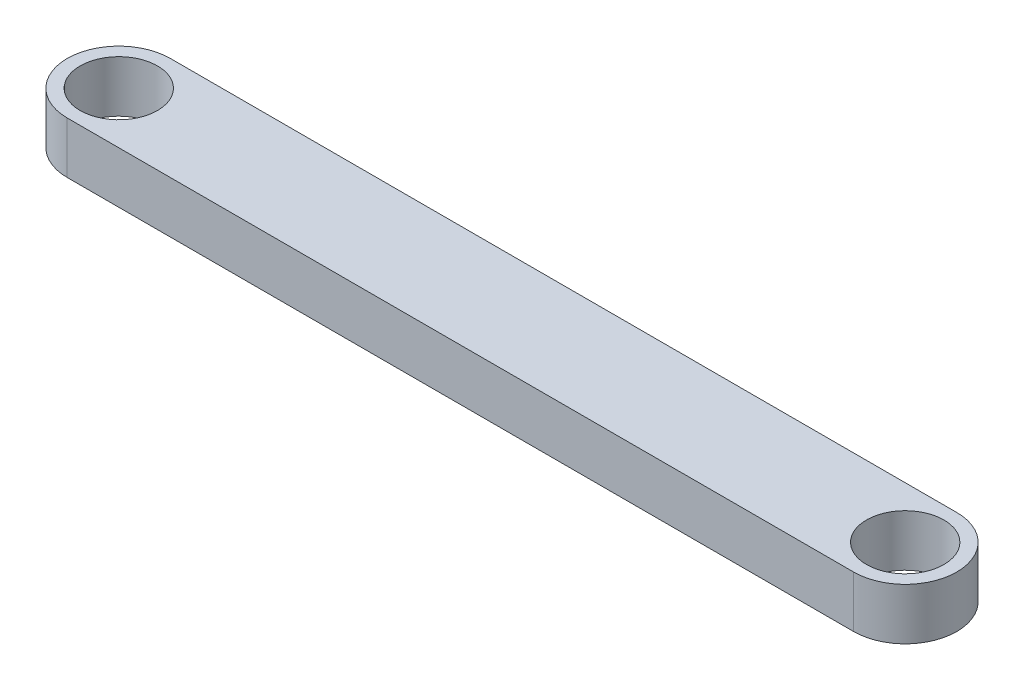
SolidWorks part; units mm, degrees
ref_plane "Front Plane" through (0, 0, 0) normal (0, 0, 1) x (1, 0, 0)
ref_plane "Top Plane" through (0, 0, 0) normal (0, 1, 0) x (1, 0, 0)
ref_plane "Right Plane" through (0, 0, 0) normal (1, 0, 0) x (0, 0, -1)
sketch "Sketch1" plane through (0, 0, 0) normal (0, 1, 0) x (1, 0, 0)
  line L0 (-97.4302, 24.3369) -> (-66.9302, 24.3369)
  line L1 (-66.9302, 20.3369) -> (-97.4302, 20.3369)
  arc A0 (-97.4302, 24.3369) -> (-97.4302, 20.3369) centre (-97.4302, 22.3369) ccw
  arc A1 (-66.9302, 20.3369) -> (-66.9302, 24.3369) centre (-66.9302, 22.3369) ccw
  circle A2 centre (-97.4302, 22.3369) radius 1.5
  circle A3 centre (-66.9302, 22.3369) radius 1.5
  dimension "D1" = 4
  dimension "D2" = 30.5
extrude "Boss-Extrude2" add sketch "Sketch1" along normal blind 2
